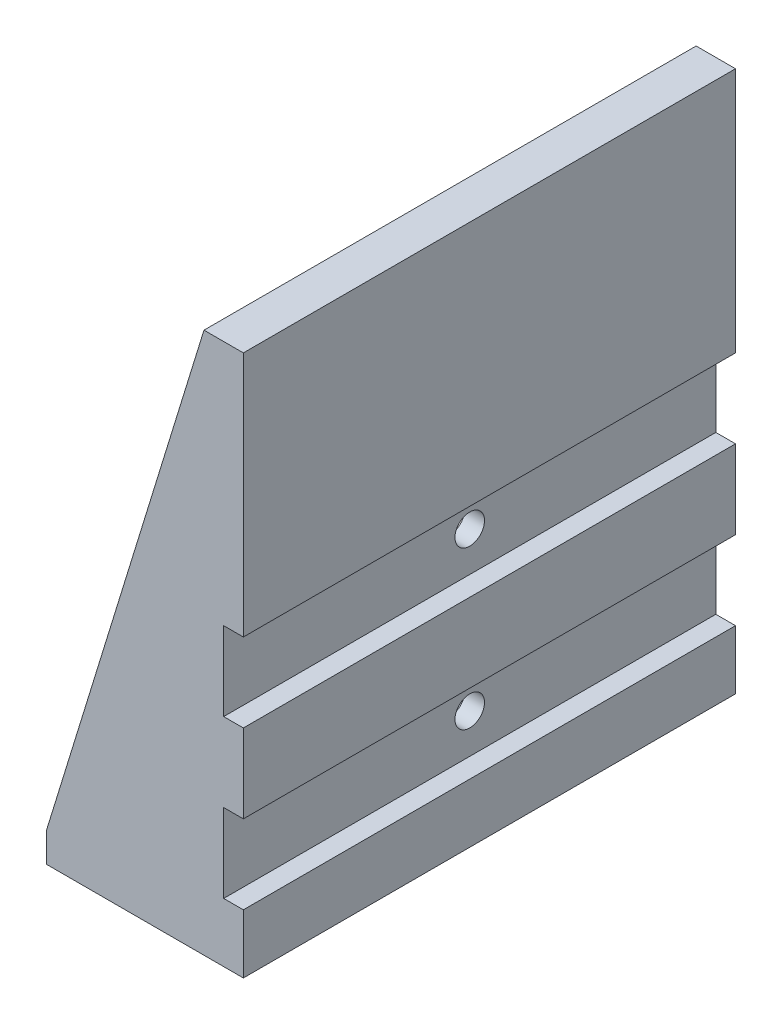
SolidWorks part; units mm, degrees
ref_plane "Front Plane" through (0, 0, 0) normal (0, 0, 1) x (1, 0, 0)
ref_plane "Top Plane" through (0, 0, 0) normal (0, 1, 0) x (1, 0, 0)
ref_plane "Right Plane" through (0, 0, 0) normal (1, 0, 0) x (0, 0, -1)
sketch "Sketch1" plane through (0, 0, 0) normal (0, 0, 1) x (1, 0, 0)
  line L0 (-10, 0) -> (10, 0)
  line L1 (-10, 0) -> (-10, 3)
  line L2 (-10, 3) -> (6, 55)
  line L3 (-10, 3) -> (23.3287, 3) construction
  line L4 (6, 55) -> (10, 55)
  line L5 (10, 0) -> (10, 55)
  point P4 (0, 0)
  dimension "D1" = 20
  dimension "D2" = 3
  dimension "D3" = 55
  dimension "D4" = 4
extrude "Boss-Extrude1" add sketch "Sketch1" along normal blind 50
sketch "Sketch2" plane through (10, 0, 0) normal (1, 0, 0) x (0, 0, -1)
  line L0 (-50, 0) -> (-50, 55) construction
  line L1 (-50, 14) -> (0, 14)
  line L2 (-50, 14) -> (-50, 6)
  line L3 (-50, 6) -> (0, 6)
  line L4 (0, 14) -> (0, 6)
  line L5 (0, 0) -> (0, 55) construction
  line L6 (-50, 0) -> (0, 0) construction
  line L8 (-50, 22) -> (0, 22)
  line L9 (-50, 22) -> (-50, 30)
  line L10 (-50, 30) -> (0, 30)
  line L11 (0, 22) -> (0, 30)
  dimension "D1" = 8
  dimension "D2" = 6
  dimension "D3" = 8
  dimension "D4" = 8
extrude "Cut-Extrude1" cut sketch "Sketch2" against normal blind 2
sketch "Sketch3" plane through (-9.9784, 3.0703, 0) normal (-0.9558, 0.2941, 0) x (0, 0, 1)
  line L0 (2.5, 54.3324) -> (2.5, -0.0735)
  line L1 (2.5, -0.0735) -> (17.5, -0.0735)
  line L2 (17.5, -0.0735) -> (17.5, 54.3324)
  line L4 (50, -0.0735) -> (0, -0.0735) construction
  line L5 (2.5, 54.3324) -> (17.5, 54.3324)
  line L6 (50, 54.3324) -> (0, 54.3324) construction
ref_plane "Plane1" through (-10, 0, 0) normal (-1, 0, 0) x (0, 0, 1)
sketch "Sketch4" plane through (-10, 0, 0) normal (-1, 0, 0) x (0, 0, 1)
  line L0 (2.5, 55) -> (2.5, 3) construction
  line L4 (2.5, 55) -> (2.5, 3)
  line L5 (2.5, 55) -> (47.5, 55)
  line L6 (50, 55) -> (0, 55) construction
  line L7 (47.5, 55) -> (47.5, 3)
  line L9 (0, 55) -> (0, 3) construction
  line L10 (50, 3) -> (0, 3) construction
  line L11 (47.5, 3) -> (2.5, 3)
  line L12 (50, 55) -> (50, 3) construction
  dimension "D1" = 2.5
  dimension "D2" = 2.5
extrude "Cut-Extrude2" cut sketch "Sketch4" against normal up to vertex (16 mm away) up to point (6, 55, 2.5)
sketch "Sketch6" plane through (8, 0, 0) normal (1, 0, 0) x (0, 0, -1)
  line L0 (-50, 26) -> (0, 26) construction
  line L1 (-50, 30) -> (-50, 22) construction
  line L2 (0, 22) -> (0, 30) construction
  line L3 (-50, 10) -> (0, 10) construction
  line L4 (-50, 14) -> (-50, 6) construction
  line L5 (0, 6) -> (0, 14) construction
  circle A0 centre (-25, 26) radius 1.5
  circle A1 centre (-25, 10) radius 1.5
  dimension "D1" = 3
extrude "Cut-Extrude4" cut sketch "Sketch6" against normal up to surface (2 mm away) up to face at (6, 29, 25)
sketch "草图2" plane through (0, 3, 0) normal (0, 1, 0) x (1, 0, 0)
  line L0 (-7, -25) -> (3, -25) construction
  line L1 (-7, -24) -> (3, -24)
  line L2 (-7, -26) -> (3, -26)
  line L3 (6, -2.5) -> (6, -47.5) construction
  line L4 (6, -2.5) -> (6, -47.5) construction
  arc A0 (-7, -24) -> (-7, -26) centre (-7, -25) ccw
  arc A1 (3, -26) -> (3, -24) centre (3, -25) ccw
  point P2 (-2, -25)
  point P13 (6, -25)
  dimension "D2" = 1
  dimension "D1" = 10
  dimension "D3" = 3
extrude "切除-拉伸2" cut sketch "草图2" against normal blind 16
